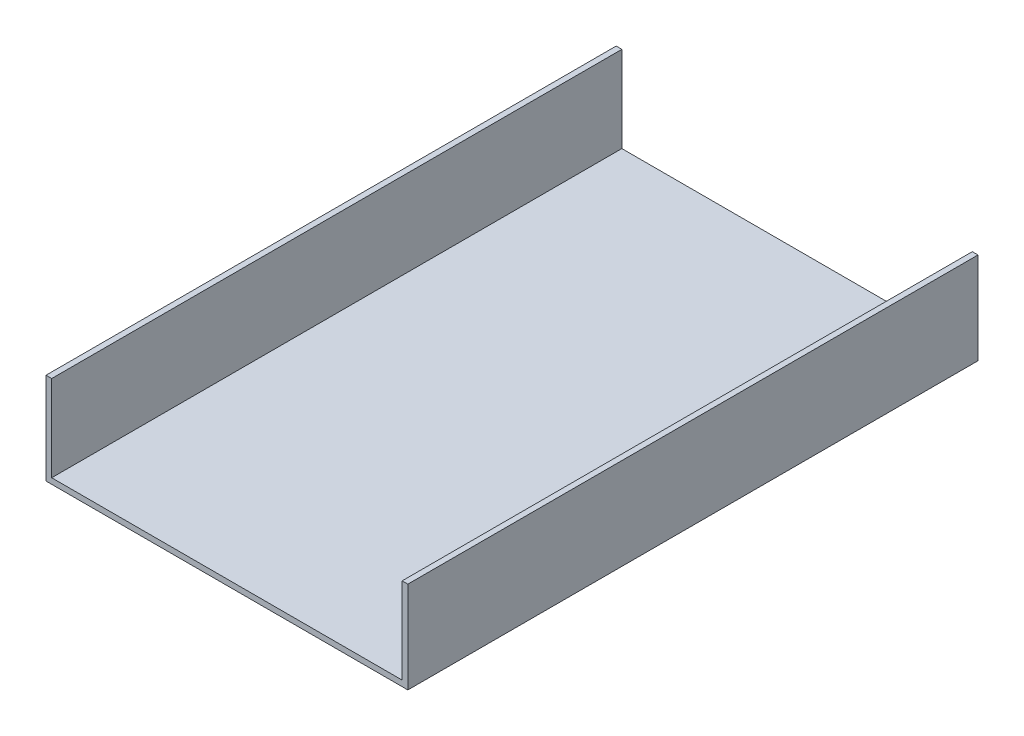
SolidWorks part; units mm, degrees
ref_plane "Alzado" through (0, 0, 0) normal (0, 0, 1) x (1, 0, 0)
ref_plane "Planta" through (0, 0, 0) normal (0, 1, 0) x (1, 0, 0)
ref_plane "Vista lateral" through (0, 0, 0) normal (1, 0, 0) x (0, 0, -1)
sketch "Croquis1" plane through (0, 0, 0) normal (0, 0, 1) x (1, 0, 0)
  line L0 (0, -55) -> (0, 55) construction
  line L1 (-50.77, 12.86) -> (50.77, 12.86)
  line L2 (-50.77, 12.86) -> (-50.77, -12.86)
  line L3 (-50.77, -12.86) -> (50.77, -12.86)
  line L4 (50.77, 12.86) -> (50.77, -12.86)
  line L5 (-49.17, 11.26) -> (49.17, 11.26)
  line L6 (-49.17, 11.26) -> (-49.17, -11.26)
  line L7 (-49.17, -11.26) -> (49.17, -11.26)
  line L8 (49.17, 11.26) -> (49.17, -11.26)
  line L9 (55, 0) -> (-55, 0) construction
  point P8 (0, 12.86)
  point P9 (-50.77, 0)
  dimension "D1" = 25.72
  dimension "D2" = 101.54
  dimension "D3" = 1.6
  dimension "D4" = 1.6
  dimension "D5" = 1.6
  dimension "D6" = 1.6
extrude "Saliente-Extruir1" add sketch "Croquis1" along normal mid plane 160
sketch "Croquis2" plane through (0, 12.86, 0) normal (0, 1, 0) x (1, 0, 0)
  line L0 (50.77, 80) -> (-50.77, 80) construction
  line L1 (-49.17, 80) -> (49.17, 80)
  line L2 (-49.17, 80) -> (-49.17, -80)
  line L3 (-49.17, -80) -> (49.17, -80)
  line L4 (49.17, 80) -> (49.17, -80)
  line L5 (50.77, -80) -> (50.77, 80) construction
  line L6 (-50.77, -80) -> (-50.77, 80) construction
  line L7 (50.77, -80) -> (-50.77, -80) construction
  dimension "D1" = 0
  dimension "D2" = 1.6
  dimension "D3" = 1.6
  dimension "D4" = 0
extrude "Cortar-Extruir1" cut sketch "Croquis2" against normal blind 11.1
